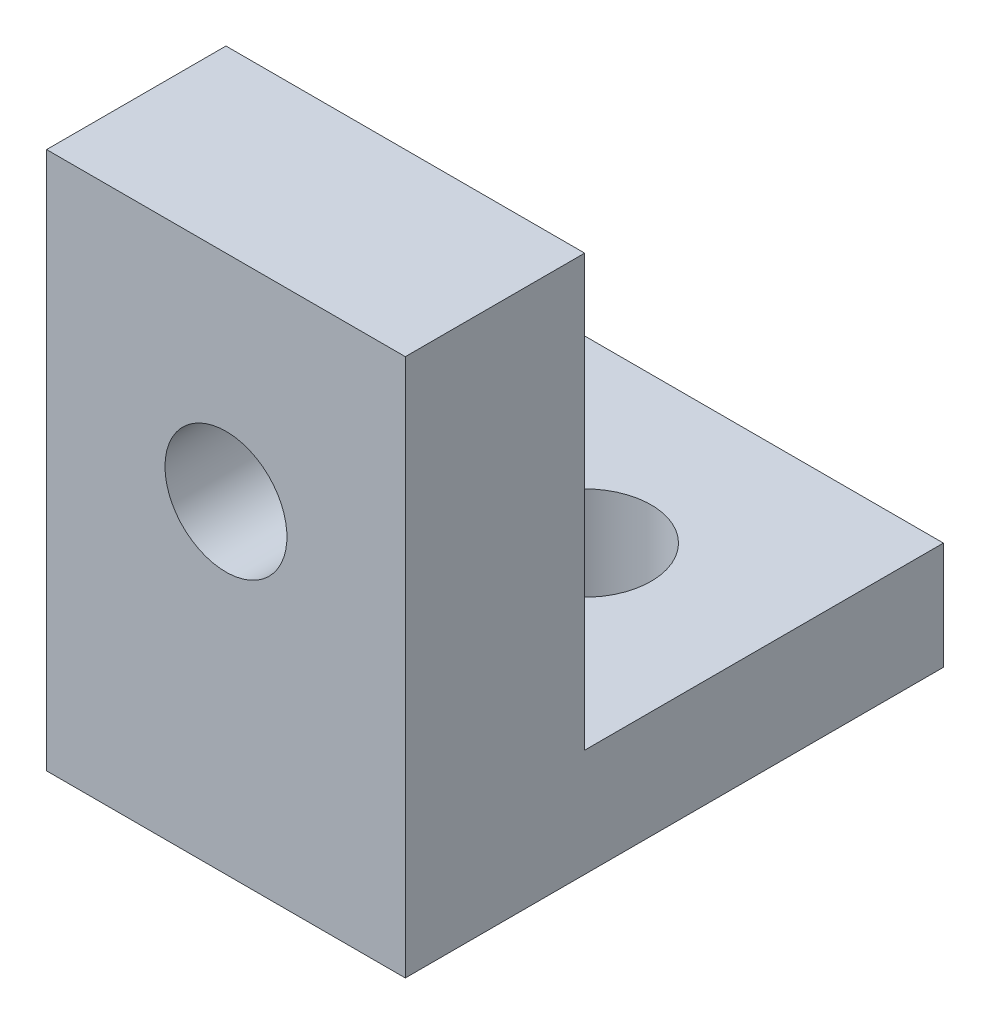
SolidWorks part; units mm, degrees
material "Onyx"
ref_plane "Front Plane" through (0, 0, 0) normal (0, 0, 1) x (1, 0, 0)
ref_plane "Top Plane" through (0, 0, 0) normal (0, 1, 0) x (1, 0, 0)
ref_plane "Right Plane" through (0, 0, 0) normal (1, 0, 0) x (0, 0, -1)
sketch "Sketch1" plane through (0, 0, 0) normal (1, 0, 0) x (0, 0, -1)
  line L0 (-5, 12) -> (0, 12)
  line L1 (0, 12) -> (0, 0)
  line L2 (0, 0) -> (10, 0)
  line L3 (10, 0) -> (10, -3)
  line L4 (10, -3) -> (-5, -3)
  line L5 (-5, -3) -> (-5, 12)
  dimension "D1" = 5
  dimension "D2" = 3
  dimension "D3" = 15
  dimension "D4" = 15
extrude "Boss-Extrude1" add sketch "Sketch1" along normal blind 10
sketch "Sketch2" plane through (0, 0, 0) normal (0, 1, 0) x (1, 0, 0)
  line L0 (0, 10) -> (10, 0) construction
  line L1 (10, 10) -> (0, 0) construction
  circle A0 centre (5, 5) radius 1.85
  dimension "D1" = 3.7
extrude "Cut-Extrude1" cut sketch "Sketch2" against normal through all
sketch "Sketch4" plane through (0, 0, 0) normal (0, 0, -1) x (-1, 0, 0)
  line L0 (-10, 12) -> (0, 0) construction
  line L1 (0, 12) -> (-10, 0) construction
  circle A0 centre (-5, 6) radius 1.7
  dimension "D1" = 3.4
extrude "Cut-Extrude2" cut sketch "Sketch4" against normal through all
sketch "Sketch5" plane through (0, 0, 0) normal (0, 0, -1) x (-1, 0, 0)
  line L0 (-10, 12) -> (0, 12) construction
  line L1 (-3.3257, 3.1) -> (-1.6514, 6)
  line L2 (-1.6514, 6) -> (-3.3257, 8.9)
  line L3 (-3.3257, 8.9) -> (-6.6743, 8.9)
  line L4 (-6.6743, 8.9) -> (-8.3486, 6)
  line L5 (-8.3486, 6) -> (-6.6743, 3.1)
  line L6 (-6.6743, 3.1) -> (-3.3257, 3.1)
  circle A0 centre (-5, 6) radius 2.9 construction
  dimension "D1" = 5.8
extrude "Cut-Extrude3" cut sketch "Sketch5" against normal blind 2.5
